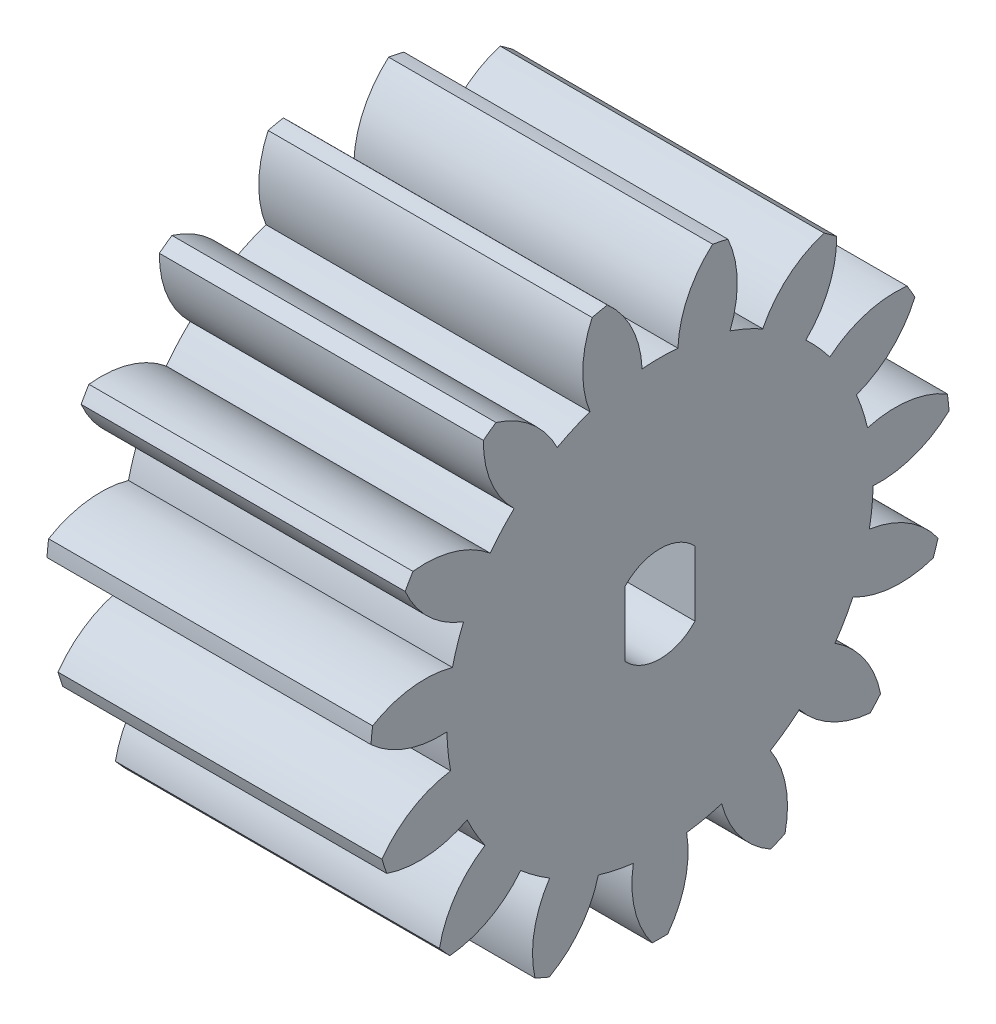
SolidWorks part; units mm, degrees
ref_plane "Plane1" through (0, 0, 0) normal (0, 0, 1) x (1, 0, 0)
ref_plane "Plane2" through (0, 0, 0) normal (0, 1, 0) x (1, 0, 0)
ref_plane "Plane3" through (0, 0, 0) normal (1, 0, 0) x (0, 0, -1)
sketch "HoldingSke" plane through (0, 0, 0) normal (0, 1, 0) x (1, 0, 0)
  line L0 (0, 0) -> (0.483, -0.1294)
  line L1 (-15, 0) -> (100, 0) construction
  line L2 (0, 0) -> (-2.1039, 2.3779)
  line L3 (0, 0) -> (-11.863, 4.5341)
  line L4 (0, 0) -> (8.3417, 2.2352)
  line L5 (0, 0) -> (-46.8476, -17.4728)
  line L6 (0, 0) -> (-4.1448, -2.7965)
  line L7 (-2.1039, 2.3779) -> (8.6586, 51.2059)
  line L8 (-76.2, 54.61) -> (-76.1, 54.61)
  line L9 (-71.009, 38.7566) -> (-53.1078, 45.2721)
  line L10 (-76.2, 71.12) -> (104.1128, 71.12)
  line L11 (0, 0) -> (-5, 0)
  line L12 (-76.2, 101.6) -> (-76.133, 101.6)
  line L13 (24.9733, 27.94) -> (52.9518, 28.4284)
  line L14 (24.9733, 27.94) -> (24.9743, 27.94)
  line L15 (24.9733, 27.94) -> (100.4006, 29.5858)
  line L16 (-63.627, -2) -> (-12.827, -2)
  circle A0 centre (0, 0) radius 0.4
  circle A1 centre (0, 0) radius 12.499
  circle A2 centre (0, 0) radius 37.5
  circle A3 centre (0, 0) radius 0.4
  dimension "MHD" = 24.998
  dimension "Hub_dia" = 75
  dimension "Bore" = 0.8
  dimension "MBD" = 0.8
  dimension "Num_teeth" = 15
  dimension "Pitch" = 0.5
  dimension "Overall_len" = 50
  dimension "Show_teeth" = 15
  dimension "Thickness" = 5
  dimension "OAL" = 50.0001
  dimension "T_dim" = 0.1
  dimension "Ap" = 20
  dimension "H" = 19.05
  dimension "Pitch_radius" = 180.3128
  dimension "Width" = 5
  dimension "Backlash" = 0.067
  dimension "Addendum_fac" = 1
  dimension "Dedendum_fac" = 1.25
  dimension "Clearance_fac" = 0.25
  dimension "Dedendum_add" = 0.001
  dimension "Module" = 2
sketch "BasProSke" plane through (0, 0, 0) normal (0, 1, 0) x (1, 0, 0)
  line L0 (-10, 0) -> (60, 0) construction
  line L1 (0, 0) -> (0, 17)
  line L2 (0, 0) -> (19, 0)
  line L3 (19, 0) -> (19, 17)
  line L4 (19, 17) -> (0, 17)
  dimension "Thickness" = 19
  dimension "Diameter" = 34
revolve "Base-Revolve" add sketch "BasProSke" angle 360 about L0
sketch "TooCutSke" plane through (0, 0, 0) normal (1, 0, 0) x (0, 0, -1)
  line L1 (0, 0) -> (0, 107) construction
  line L2 (0, 0) -> (-1.6851, 14.905) construction
  line L3 (0, 0) -> (-6.2081, 29.2069) construction
  line L4 (-1.6851, 14.905) -> (-3.1041, 14.6034) construction
  arc A0 (1.0501, 12.4548) -> (-1.0501, 12.4548) centre (0, 0) ccw
  arc A1 (3.1109, 16.7388) -> (-3.1109, 16.7388) centre (0, 0) ccw
  circle A2 centre (0, 0) radius 15 construction
  circle A3 centre (0, 0) radius 14.0954 construction
  arc A4 (-1.0501, 12.4548) -> (-3.1109, 16.7388) centre (-7.045, 12.2085) ccw
  arc A5 (3.1109, 16.7388) -> (1.0501, 12.4548) centre (7.045, 12.2085) ccw
  dimension "Root_dia" = 24.998
  dimension "Overcut_dia" = 34.0508
  dimension "Pitch_dia" = 30
  dimension "Base_dia" = 28.1908
  dimension "Flank_rad" = 6
  dimension "Half_ang" = 12
  dimension "Half_CT" = 1.4507
extrude "ToothCut" cut sketch "TooCutSke" along normal through all
fillet "Breaks" [suppressed] radius 0.04
fillet "RootFillets" [suppressed] radius 0.501
pattern_circular "TeethCuts" count 15 every 24 about axis through (-10, 0, 0) along (1, 0, 0) of "ToothCut", "RootFillets", "Breaks"
sketch "HubNeaOneSke" plane through (0, 0, 0) normal (-1, 0, 0) x (0, 0, 1)
  circle A0 centre (0, 0) radius 12.499
  dimension "Diameter" = 24.998
extrude "HubNearOne" [suppressed] add sketch "HubNeaOneSke" along normal blind 31.0001
sketch "HubNeaBotSke" plane through (0, 0, 0) normal (-1, 0, 0) x (0, 0, 1)
  circle A0 centre (0, 0) radius 12.499
  dimension "Diameter" = 24.998
extrude "HubNearBoth" [suppressed] add sketch "HubNeaBotSke" along normal blind 15.5
ref_plane "FarPln" through (19, 0, 0) normal (1, 0, 0) x (0, 0, -1)
sketch "HubFarSke" plane through (19, 0, 0) normal (1, 0, 0) x (0, 0, -1)
  circle A0 centre (0, 0) radius 12.499
  dimension "Diameter" = 24.998
extrude "HubFar" [suppressed] add sketch "HubFarSke" along normal blind 15.5
sketch "BorSke" plane through (0, 0, 0) normal (1, 0, 0) x (0, 0, -1)
  circle A0 centre (0, 0) radius 0.4
  dimension "Diameter" = 0.8
extrude "Bore" cut sketch "BorSke" along normal mid plane 100.0001
sketch "KeySke" plane through (0, 0, 0) normal (1, 0, 0) x (0, 0, -1)
  line L0 (-0.05, 0) -> (-0.05, 0.5)
  line L1 (-0.05, 0.5) -> (0.05, 0.5)
  line L2 (0.05, 0.5) -> (0.05, 0)
  line L3 (0, 0) -> (0, 34) construction
  line L4 (-0.05, 0) -> (0.05, 0)
  dimension "Offset" = 0.5
  dimension "Width" = 0.1
extrude "Keyway" [suppressed] cut sketch "KeySke" along normal mid plane 100.0001
pattern_circular "Keyway2" [suppressed] count 2 every 90 about axis through (-10, 0, 0) along (1, 0, 0)
sketch "Sketch1" plane through (0, 0, 0) normal (-1, 0, 0) x (0, 0, 1)
  line L1 (2.05, -1.9072) -> (-2.05, -1.9072) construction
  line L2 (2.05, -1.9072) -> (2.05, 1.9072)
  line L3 (2.05, 1.9072) -> (-2.05, 1.9072) construction
  line L4 (-2.05, -1.9072) -> (-2.05, 1.9072)
  line L5 (2.05, -1.9072) -> (-2.05, 1.9072) construction
  line L6 (2.05, 1.9072) -> (-2.05, -1.9072) construction
  circle A0 centre (0, 0) radius 2.8 construction
  arc A1 (-2.05, -1.9072) -> (2.05, -1.9072) centre (0, 0) ccw
  arc A2 (-2.05, 1.9072) -> (2.05, 1.9072) centre (0, 0) cw
  dimension "D1" = 2.8
  dimension "D2" = 4.1
extrude "Cut-Extrude1" cut sketch "Sketch1" against normal up to next
equation "' \"Module@HoldingSke\" = 6.35"
equation "' \"Num_teeth@HoldingSke\" = 12"
equation "' \"Ap@HoldingSke\" =  20"
equation "' \"Ap@HoldingSke\" = 20"
equation "' \"Width@HoldingSke\" = 0.5 * 25.4"
equation "' \"Hub_dia@HoldingSke\"= 1 * 25.4"
equation "' \"Hub_dia@HoldingSke\" = 1 * 25.4"
equation "' \"Overall_len@HoldingSke\" = 1.0 * 25.4"
equation "' \"Bore@HoldingSke\" = 0.75 * 25.4"
equation "' \"T_dim@HoldingSke\" = 0.1 * 25.4"
equation "' \"Width@KeySke\" = 0.25 * 25.4"
equation "' \"Show_teeth@HoldingSke\" = 13"
equation "' \"Backlash@HoldingSke\" = 0.009 * 25.4"
equation "' \"Addendum_fac@HoldingSke\" = 1.0"
equation "' \"Dedendum_fac@HoldingSke\" = 1.25"
equation "' \"Dedendum_add@HoldingSke\" = 0.00005 * 25.4"
equation "' \"Clearance_fac@HoldingSke\" = 0.25"
equation "\"Pitch@HoldingSke\" = 1 / \"Module@HoldingSke\""
equation "\"Overcut_dia@TooCutSke\" = (\"Num_teeth@HoldingSke\" + 2 * \"Addendum_fac@HoldingSke\") / \"Pitch@HoldingSke\" + 0.002 * 25.4"
equation "\"Pitch_dia@TooCutSke\" = \"Num_teeth@HoldingSke\" / \"Pitch@HoldingSke\""
equation "\"Base_dia@TooCutSke\" = \"Num_teeth@HoldingSke\" / \"Pitch@HoldingSke\" * cos((\"Ap@HoldingSke\"  * 3.14159265 / 180))"
equation "\"Root_dia@TooCutSke\" = (\"Num_teeth@HoldingSke\" + 2) / \"Pitch@HoldingSke\" - 2 * (\"Addendum_fac@HoldingSke\" + \"Dedendum_fac@HoldingSke\") / \"Pitch@HoldingSke\" - \"Dedendum_add@HoldingSke\" * 2"
equation "\"Half_ang@TooCutSke\" = 180 / \"Num_teeth@HoldingSke\""
equation "\"Half_CT@TooCutSke\" = \"Num_teeth@HoldingSke\" / \"Pitch@HoldingSke\" * sin((3.14159265 / 2 / \"Num_teeth@HoldingSke\")) / 2 - 7 * \"Backlash@HoldingSke\" / 4"
equation "\"Flank_rad@TooCutSke\" = \"Num_teeth@HoldingSke\" / \"Pitch@HoldingSke\" / 5"
equation "\"Radius@RootFillets\" = \"Clearance_fac@HoldingSke\" / \"Pitch@HoldingSke\" + \"Dedendum_add@HoldingSke\""
equation "\"Break_rad@Breaks\" = 0.02 / \"Pitch@HoldingSke\""
equation "\"Thickness@HoldingSke\" = \"Width@HoldingSke\""
equation "\"OAL@HoldingSke\" = \"Thickness@HoldingSke\""
equation "\"MHD@HoldingSke\" = (\"Num_teeth@HoldingSke\" + 2) / \"Pitch@HoldingSke\" - 2 * (\"Addendum_fac@HoldingSke\" + \"Dedendum_fac@HoldingSke\")  / \"Pitch@HoldingSke\" - \"Dedendum_add@HoldingSke\" * 2"
equation "\"MBD@HoldingSke\" = (\"Num_teeth@HoldingSke\" + 2) / \"Pitch@HoldingSke\" - 2 * (\"Addendum_fac@HoldingSke\" + \"Dedendum_fac@HoldingSke\")  / \"Pitch@HoldingSke\" - \"Dedendum_add@HoldingSke\" * 2 - 0.002 * 25.4"
equation "\"MHD@HoldingSke\" = ((sgn( \"MHD@HoldingSke\" - \"Hub_dia@HoldingSke\" )-1)*( \"MHD@HoldingSke\" - \"Hub_dia@HoldingSke\" ))/-2+ \"Hub_dia@HoldingSke\""
equation "\"MBD@HoldingSke\" = ((sgn( \"MBD@HoldingSke\" - \"Bore@HoldingSke\" )-1)*( \"MBD@HoldingSke\" - \"Bore@HoldingSke\" ))/-2+ \"Bore@HoldingSke\""
equation "\"OAL@HoldingSke\" = ((sgn( \"OAL@HoldingSke\" - \"Overall_len@HoldingSke\" )+1)*( \"OAL@HoldingSke\" - \"Overall_len@HoldingSke\" ))/2 + \"Overall_len@HoldingSke\" + 0.000002 * 25.4"
equation "\"Num_teeth@TeethCuts\" = int( \"Show_teeth@HoldingSke\" ) + 1"
equation "\"Num_teeth@TeethCuts\" = ((sgn( \"Num_teeth@TeethCuts\" - \"Num_teeth@HoldingSke\" )-1)*( \"Num_teeth@TeethCuts\" - \"Num_teeth@HoldingSke\" ))/-2+ \"Num_teeth@HoldingSke\""
equation "\"Num_teeth@TeethCuts\" = ((sgn( \"Num_teeth@TeethCuts\" - 2.0)+1)*( \"Num_teeth@TeethCuts\" - 2.0))/2 +2.0"
equation "\"Angle@TeethCuts\" = 360.0 / \"Num_teeth@HoldingSke\""
equation "\"Diameter@BasProSke\" = (\"Num_teeth@HoldingSke\" + 2 * \"Addendum_fac@HoldingSke\") / \"Pitch@HoldingSke\""
equation "\"Thickness@BasProSke\"=19mm"
equation "' \"Fillet_rad@BasProSke\" =  \"Thickness@HoldingSke\" * 0.05"
equation "' \"Fillet_rad@BasProSke\" = \"Thickness@HoldingSke\" * 0.05"
equation "\"MHD@HoldingSke\" = ((sgn( \"MHD@HoldingSke\" - \"Root_dia@TooCutSke\" )-1)*( \"MHD@HoldingSke\" - \"Root_dia@TooCutSke\" ))/-2+ \"Root_dia@TooCutSke\""
equation "\"Diameter@HubNeaOneSke\" = \"MHD@HoldingSke\""
equation "\"Length@HubNearOne\" = \"OAL@HoldingSke\" - \"Thickness@BasProSke\""
equation "\"Diameter@HubNeaBotSke\" = \"MHD@HoldingSke\""
equation "\"Length@HubNearBoth\" = ( \"OAL@HoldingSke\" - \"Thickness@BasProSke\" ) / 2.0"
equation "\"Thickness@FarPln\" = \"Thickness@BasProSke\""
equation "\"Diameter@HubFarSke\" = \"MHD@HoldingSke\""
equation "\"Length@HubFar\" = ( \"OAL@HoldingSke\" - \"Thickness@BasProSke\" ) / 2.0"
equation "\"Diameter@BorSke\" = \"MBD@HoldingSke\""
equation "\"D1@Bore\" = \"OAL@HoldingSke\" * 2.0"
equation "\"D1@Keyway\" = \"OAL@HoldingSke\" * 2.0"
equation "\"Offset@KeySke\" = \"T_dim@HoldingSke\" + \"MBD@HoldingSke\" / 2.0"
